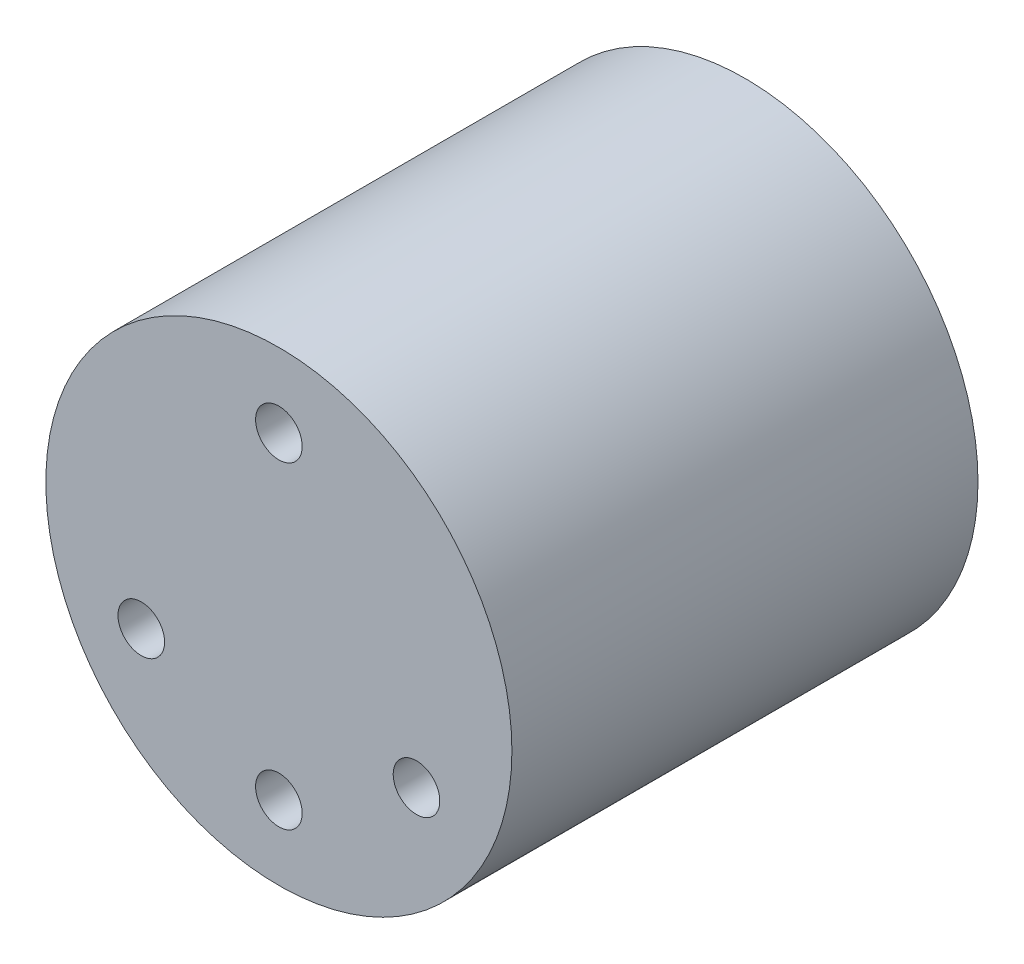
SolidWorks part; units mm, degrees
ref_plane "前视基准面" through (0, 0, 0) normal (0, 0, 1) x (1, 0, 0)
ref_plane "上视基准面" through (0, 0, 0) normal (0, 1, 0) x (1, 0, 0)
ref_plane "右视基准面" through (0, 0, 0) normal (1, 0, 0) x (0, 0, -1)
sketch "草图1" plane through (0, 0, 0) normal (0, 0, 1) x (1, 0, 0)
  line L0 (0, 0) -> (0, -7.5) construction
  line L1 (0, 0) -> (-6.4952, -3.75) construction
  line L2 (0, 7.5) -> (0, 0) construction
  circle A0 centre (0, 0) radius 11
  circle A1 centre (0, 7.5) radius 1.1
  circle A2 centre (0, -7.5) radius 1.1
  circle A3 centre (0, 0) radius 7.5 construction
  circle A4 centre (-6.4952, -3.75) radius 1.1
  circle A5 centre (6.4952, -3.75) radius 1.1
  dimension "D2" = 15
  dimension "D3" = 2.2
  dimension "D4" = 2.2
  dimension "D5" = 2.2
  dimension "D6" = 22
  dimension "D1" = 60
extrude "凸台-拉伸1" add sketch "草图1" along normal blind 22
